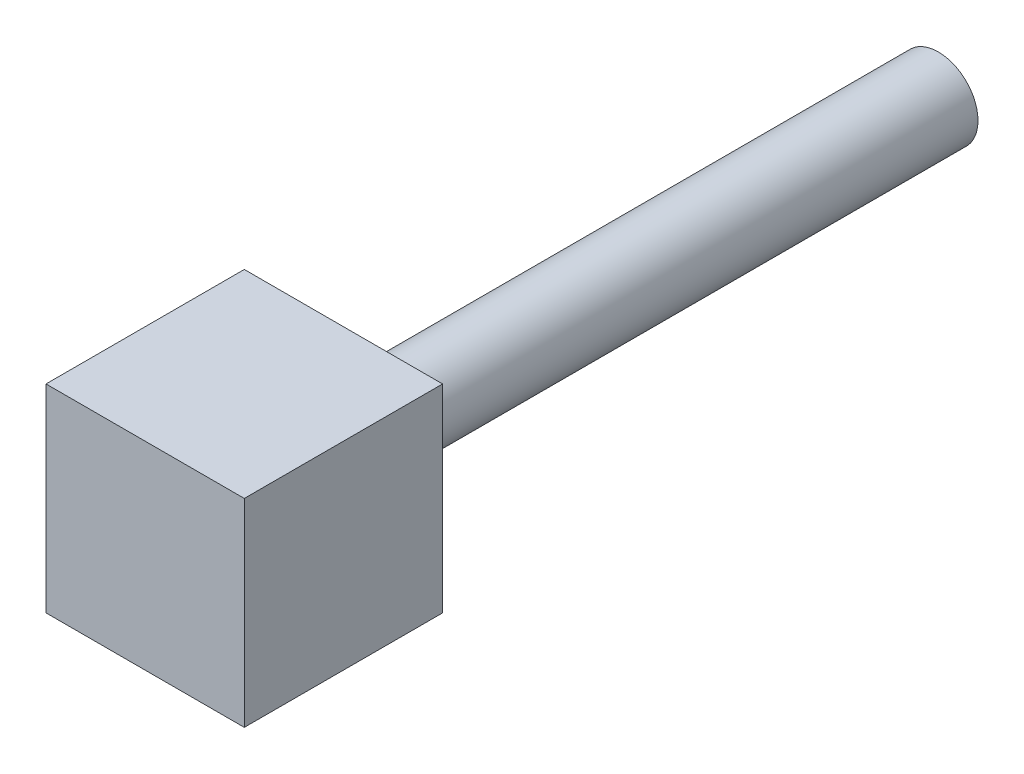
SolidWorks part; units mm, degrees
other "Markup1"
sketch "Sketch3" plane through (-4, 5.1961, 45.2154) normal (-0.458, 0.0407, 0.888) x (0.8887, -0.0036, 0.4585)
material "1060 Alloy"
ref_plane "Front Plane" through (0, 0, 0) normal (0, 0, 1) x (1, 0, 0)
ref_plane "Top Plane" through (0, 0, 0) normal (0, 1, 0) x (1, 0, 0)
ref_plane "Right Plane" through (0, 0, 0) normal (1, 0, 0) x (0, 0, -1)
sketch "Sketch1" plane through (0, 0, 0) normal (1, 0, 0) x (0, 0, -1)
  line L1 (-45.2154, 1.1961) -> (14.7846, 1.1961)
  line L2 (-45.2154, 1.1961) -> (-45.2154, 5.1961)
  line L3 (-45.2154, 5.1961) -> (14.7846, 5.1961)
  line L4 (14.7846, 1.1961) -> (14.7846, 5.1961)
  line L5 (-45.2154, 1.1961) -> (14.7846, 5.1961) construction
  line L6 (-45.2154, 5.1961) -> (14.7846, 1.1961) construction
  point P0 (-15.2154, 3.1961)
  dimension "D1" = 60
  dimension "D2" = 4
revolve "Revolve1" add sketch "Sketch1" angle 360 about L1
sketch "Sketch4" plane through (0, 0, 45.2154) normal (0, 0, 1) x (1, 0, 0)
  line L0 (0, 1.1961) -> (0, 5.1961) construction
  line L1 (-10, -8.8039) -> (10, -8.8039)
  line L2 (-10, -8.8039) -> (-10, 11.1961)
  line L3 (-10, 11.1961) -> (10, 11.1961)
  line L4 (10, -8.8039) -> (10, 11.1961)
  line L5 (-10, -8.8039) -> (10, 11.1961) construction
  line L6 (-10, 11.1961) -> (10, -8.8039) construction
  line L7 (0, 1.1961) -> (0, 5.1961) construction
  point P0 (0, 1.1961)
  dimension "D1" = 20
  dimension "D2" = 20
extrude "Boss-Extrude2" add sketch "Sketch4" along normal blind 20
